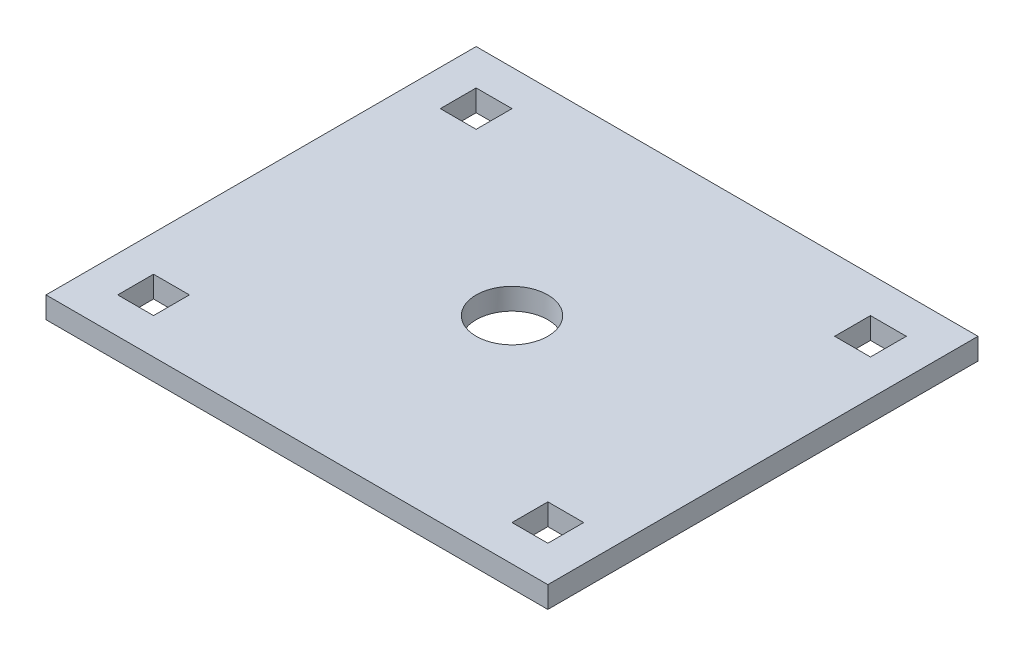
SolidWorks part; units mm, degrees
ref_plane "Front Plane" through (0, 0, 0) normal (0, 0, 1) x (1, 0, 0)
ref_plane "Top Plane" through (0, 0, 0) normal (0, 1, 0) x (1, 0, 0)
ref_plane "Right Plane" through (0, 0, 0) normal (1, 0, 0) x (0, 0, -1)
sketch "Sketch1" plane through (0, 0, 0) normal (0, 1, 0) x (1, 0, 0)
  line L1 (-88.9, -76.2) -> (88.9, -76.2)
  line L2 (-88.9, -76.2) -> (-88.9, 76.2)
  line L3 (-88.9, 76.2) -> (88.9, 76.2)
  line L4 (88.9, -76.2) -> (88.9, 76.2)
  line L5 (-88.9, -76.2) -> (88.9, 76.2) construction
  line L6 (-88.9, 76.2) -> (88.9, -76.2) construction
  point P0 (0, 0)
  dimension "D1" = 177.8
  dimension "D2" = 152.4
extrude "Boss-Extrude1" add sketch "Sketch1" along normal blind 7.62
sketch "Sketch2" plane through (0, 7.62, 0) normal (0, 1, 0) x (1, 0, 0)
  circle A0 centre (0, 0) radius 12.7
  dimension "D1" = 25.4
extrude "Cut-Extrude1" cut sketch "Sketch2" against normal up to surface (7.62 mm away) up to face at (0, 0, 0)
sketch "Sketch3" plane through (0, 7.62, 0) normal (0, 1, 0) x (1, 0, 0)
  line L0 (-76.2, -63.5) -> (-88.9, -63.5) construction
  line L1 (-76.2, -63.5) -> (-63.5, -63.5)
  line L2 (-76.2, -63.5) -> (-76.2, -50.8)
  line L3 (-76.2, -50.8) -> (-63.5, -50.8)
  line L4 (-63.5, -63.5) -> (-63.5, -50.8)
  line L5 (-88.9, 76.2) -> (-88.9, -76.2) construction
  line L6 (76.2, -50.8) -> (88.9, -50.8) construction
  line L7 (63.5, -63.5) -> (76.2, -63.5)
  line L8 (63.5, -63.5) -> (63.5, -50.8)
  line L9 (63.5, -50.8) -> (76.2, -50.8)
  line L10 (76.2, -63.5) -> (76.2, -50.8)
  line L11 (-76.2, 63.5) -> (-63.5, 63.5)
  line L12 (-76.2, 63.5) -> (-76.2, 50.8)
  line L13 (-76.2, 50.8) -> (-63.5, 50.8)
  line L14 (-63.5, 63.5) -> (-63.5, 50.8)
  line L15 (63.5, 63.5) -> (76.2, 63.5)
  line L16 (63.5, 63.5) -> (63.5, 50.8)
  line L17 (63.5, 50.8) -> (76.2, 50.8)
  line L18 (76.2, 63.5) -> (76.2, 50.8)
  line L19 (88.9, -76.2) -> (88.9, 76.2) construction
  line L20 (-76.2, 63.5) -> (-76.2, 76.2) construction
  line L21 (88.9, 76.2) -> (-88.9, 76.2) construction
  line L22 (-63.5, -63.5) -> (-63.5, -76.2) construction
  line L23 (-88.9, -76.2) -> (88.9, -76.2) construction
  dimension "D1" = 12.7
  dimension "D2" = 12.7
extrude "Cut-Extrude2" cut sketch "Sketch3" against normal through all
sketch "Sketch5" plane through (0, 7.62, 0) normal (0, 1, 0) x (1, 0, 0)
  line L0 (-63.5, -50.8) -> (-63.5, 50.8) construction
  line L1 (-50.8, 0) -> (-63.5, 0) construction
  circle A0 centre (0, 0) radius 50.8 construction
  dimension "D1" = 101.6
  dimension "D2" = 12.7
